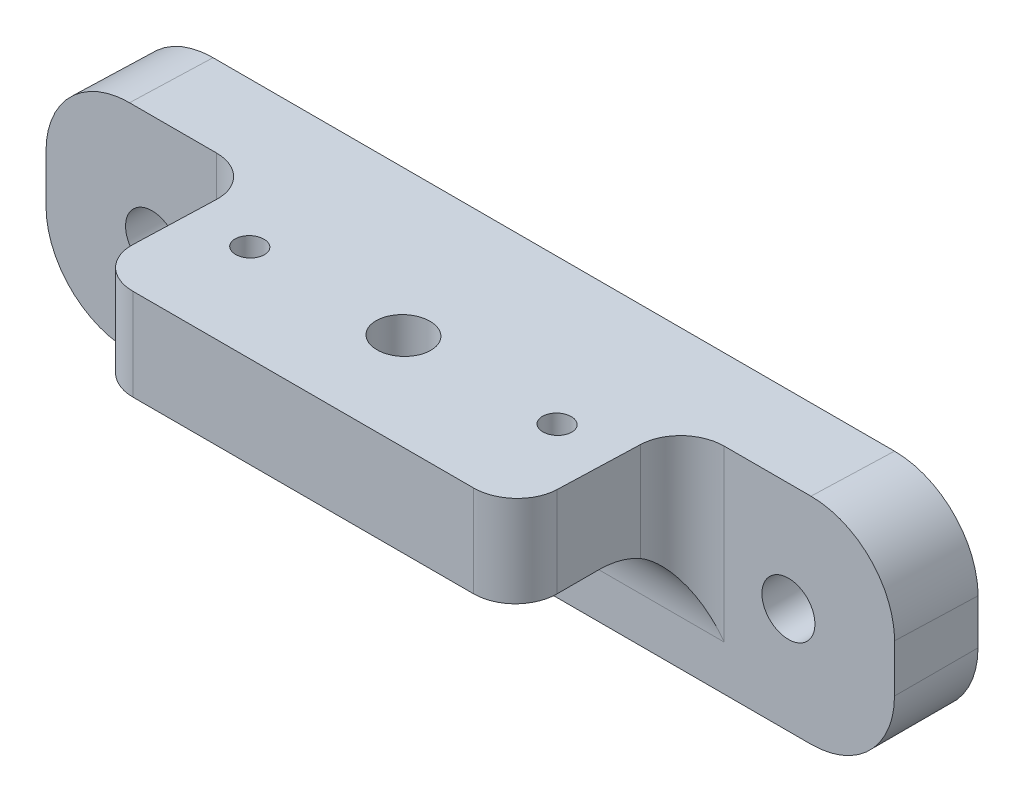
SolidWorks part; units mm, degrees
material "PETG"
ref_plane "Front Plane" through (0, 0, 0) normal (0, 0, 1) x (1, 0, 0)
ref_plane "Top Plane" through (0, 0, 0) normal (0, 1, 0) x (1, 0, 0)
ref_plane "Right Plane" through (0, 0, 0) normal (1, 0, 0) x (0, 0, -1)
sketch "Sketch1" plane through (0, 0, 0) normal (0, 0, 1) x (1, 0, 0)
  line L1 (-50.8, -12.7) -> (50.8, -12.7)
  line L2 (-50.8, -12.7) -> (-50.8, 12.7)
  line L3 (-50.8, 12.7) -> (50.8, 12.7)
  line L4 (50.8, -12.7) -> (50.8, 12.7)
  line L5 (-50.8, -12.7) -> (50.8, 12.7) construction
  line L6 (-50.8, 12.7) -> (50.8, -12.7) construction
  point P0 (0, 0)
  dimension "D1" = 25.4
  dimension "D2" = 101.6
extrude "Boss-Extrude1" add sketch "Sketch1" against normal blind 10
sketch "Sketch4" plane through (0, 12.7, 0) normal (0, 1, 0) x (1, 0, 0)
  line L0 (50.8, 0) -> (-50.8, 0) construction
  line L1 (-25.4, 0) -> (25.4, 0)
  line L2 (-25.4, 0) -> (-25.4, -20)
  line L3 (-25.4, -20) -> (25.4, -20)
  line L4 (25.4, 0) -> (25.4, -20)
  line L5 (-25.4, 0) -> (25.4, -20) construction
  line L6 (-25.4, -20) -> (25.4, 0) construction
  line L7 (50.8, 10) -> (-50.8, 10) construction
  point P4 (0, -10)
  dimension "D1" = 50.8
  dimension "D2" = 30
extrude "Boss-Extrude2" add sketch "Sketch4" against normal blind 10
sketch "Sketch8" plane through (0, 0, 0) normal (1, 0, 0) x (0, 0, -1)
  line L0 (10, 12.7) -> (-20, 13.6802)
  line L1 (-20, 13.6802) -> (-20, 12.7)
  line L2 (10, 12.7) -> (-20, 12.7)
  point P4 (-20, 12.7)
  dimension "D1" = 88.129
extrude "Boss-Extrude4" add sketch "Sketch8" along normal through all and the other way through all
sketch "Sketch9" plane through (0, 12.7, 0) normal (0, -1, 0) x (1, 0, 0)
  line L1 (-50.8, 20) -> (-25.4, 20)
  line L2 (-50.8, 20) -> (-50.8, 0)
  line L3 (-50.8, 0) -> (-25.4, 0)
  line L4 (-25.4, 20) -> (-25.4, 0)
  line L5 (50.8, 20) -> (25.4, 20)
  line L6 (50.8, 20) -> (50.8, 0)
  line L7 (50.8, 0) -> (25.4, 0)
  line L8 (25.4, 20) -> (25.4, 0)
extrude "Cut-Extrude4" cut sketch "Sketch9" against normal through all contours L5 L8 L7 L6
fillet "Fillet1" radius 10 1 edges at (0, 2.7, 0)
sketch "Sketch5" plane through (0, 2.7, 0) normal (0, 1, 0) x (1, 0, 0)
  line L0 (0, 0) -> (0, 50000) construction
  line L1 (-25.4, -20) -> (25.4, -20) construction
  circle A0 centre (0, -8) radius 3.175
  circle A2 centre (-18.4, -8) radius 1.7
  circle A3 centre (18.4, -8) radius 1.7
  dimension "D1" = 18.4
  dimension "D2" = 3.4
  dimension "D3" = 6.35
  dimension "D4" = 12
extrude "Cut-Extrude1" cut sketch "Sketch5" along normal up to next
sketch "Sketch6" plane through (0, 0, 0) normal (0, 0, 1) x (1, 0, 0)
  line L0 (0, 0) -> (0, 50000) construction
  circle A0 centre (-38.1, 0) radius 3.175
  circle A1 centre (38.1, 0) radius 3.175
  dimension "D1" = 6.35
  dimension "D2" = 38.1
extrude "Cut-Extrude2" cut sketch "Sketch6" against normal up to next
fillet "Fillet2" radius 10 4 edges at (50.8, -12.7, -5) (-50.8, -12.7, -5) (50.8, 12.8634, -5) (-50.8, 12.8634, -5)
sketch "Sketch7" plane through (0, 2.7, 0) normal (0, -1, 0) x (1, 0, 0)
  circle A0 centre (0, 8) radius 6
  circle A1 centre (-18.4, 8) radius 3
  circle A2 centre (18.4, 8) radius 3
  dimension "D1" = 12
  dimension "D2" = 6
extrude "Cut-Extrude3" cut sketch "Sketch7" along normal up to next
fillet "Fillet3" radius 5 2 edges at (25.4, 2.8634, 0) (-25.4, 2.8634, 0)
fillet "Fillet4" radius 5 2 edges at (25.4, 8.1901, 20) (-25.4, 8.1901, 20)
